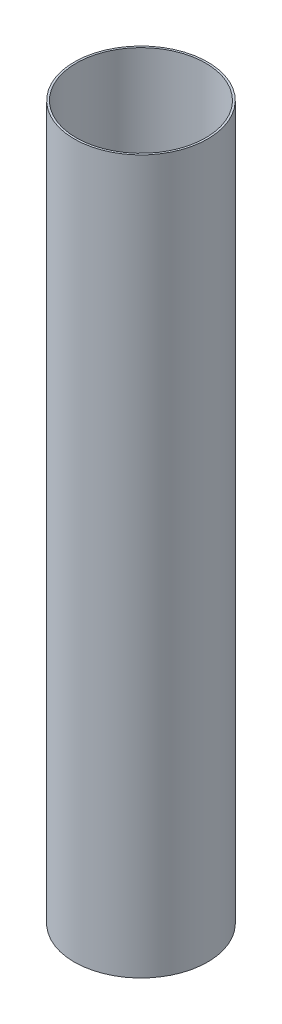
SolidWorks part; units mm, degrees
ref_plane "Front Plane" through (0, 0, 0) normal (0, 0, 1) x (1, 0, 0)
ref_plane "Top Plane" through (0, 0, 0) normal (0, 1, 0) x (1, 0, 0)
ref_plane "Right Plane" through (0, 0, 0) normal (1, 0, 0) x (0, 0, -1)
sketch "Sketch1" plane through (0, 0, 0) normal (0, 1, 0) x (1, 0, 0)
  circle A0 centre (0, 0) radius 38.15
  circle A1 centre (0, 0) radius 39.3
  dimension "D1" = 78.6
  dimension "D2" = 76.3
extrude "Boss-Extrude1" add sketch "Sketch1" along normal blind 420
ref_plane "Plane1" through (-27.7893, 0, 27.7893) normal (-0.7071, 0, 0.7071) x (0, -1, 0)
